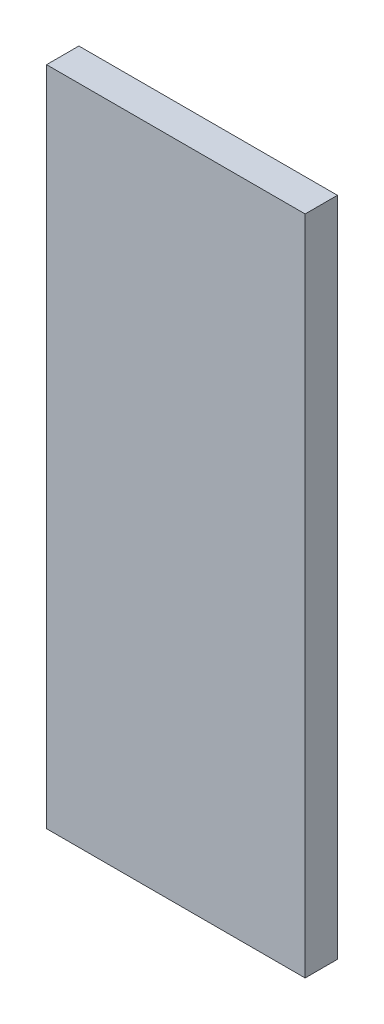
SolidWorks part; units mm, degrees
material "Aleación 1060"
ref_plane "Alzado" through (0, 0, 0) normal (0, 0, 1) x (1, 0, 0)
ref_plane "Planta" through (0, 0, 0) normal (0, 1, 0) x (1, 0, 0)
ref_plane "Vista lateral" through (0, 0, 0) normal (1, 0, 0) x (0, 0, -1)
sketch "Croquis1" plane through (0, 0, 0) normal (0, 0, 1) x (1, 0, 0)
  line L1 (50.8, -130) -> (-50.8, -130)
  line L2 (50.8, -130) -> (50.8, 130)
  line L3 (50.8, 130) -> (-50.8, 130)
  line L4 (-50.8, -130) -> (-50.8, 130)
  line L5 (50.8, -130) -> (-50.8, 130) construction
  line L6 (50.8, 130) -> (-50.8, -130) construction
  point P0 (0, 0)
  dimension "D1" = 260
  dimension "D2" = 101.6
extrude "Saliente-Extruir1" add sketch "Croquis1" along normal blind 12.7
